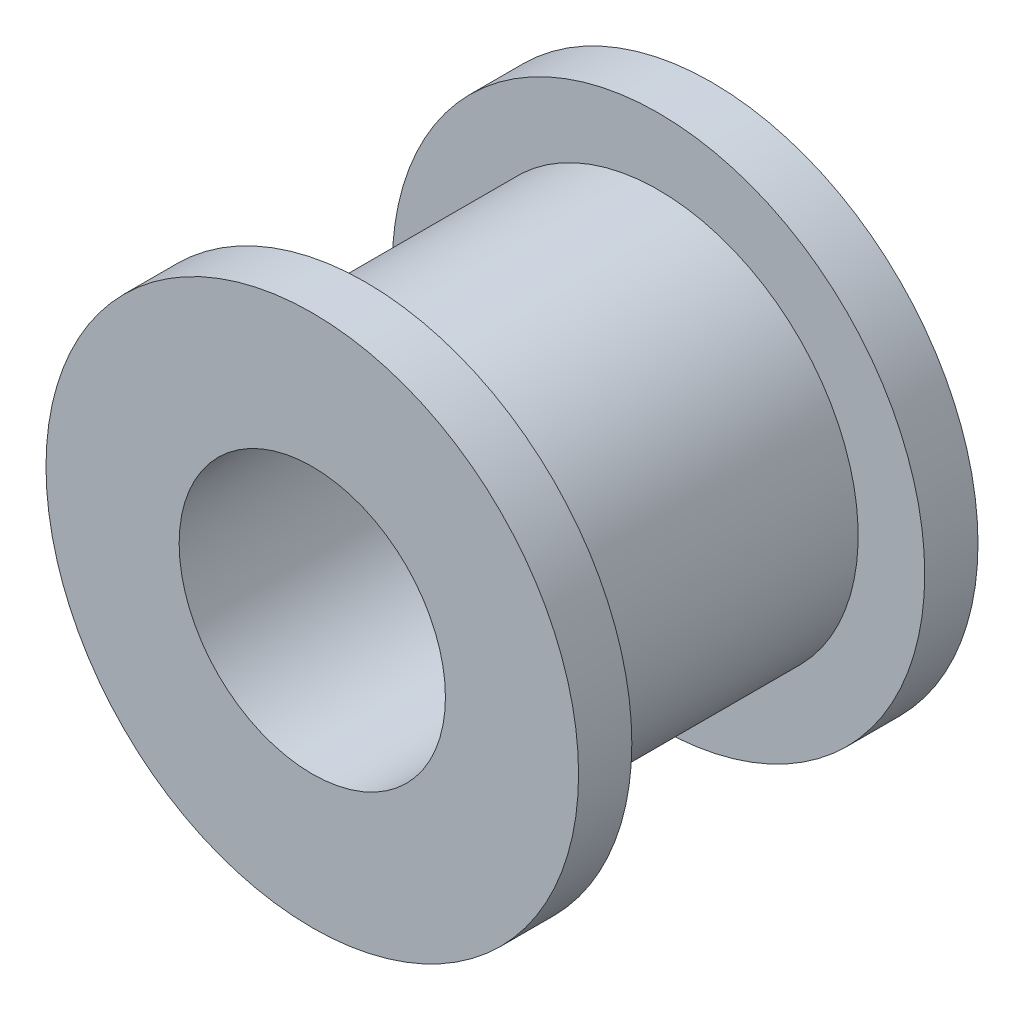
SolidWorks part; units mm, degrees
material "Nylon 6/10"
ref_plane "Front Plane" through (0, 0, 0) normal (0, 0, 1) x (1, 0, 0)
ref_plane "Top Plane" through (0, 0, 0) normal (0, 1, 0) x (1, 0, 0)
ref_plane "Right Plane" through (0, 0, 0) normal (1, 0, 0) x (0, 0, -1)
sketch "Sketch1" plane through (0, 0, 0) normal (0, 0, 1) x (1, 0, 0)
  circle A0 centre (0, 0) radius 5
  circle A1 centre (0, 0) radius 7.5
  dimension "D1" = 10
  dimension "D2" = 15
extrude "Boss-Extrude1" add sketch "Sketch1" along normal blind 11
sketch "Sketch2" plane through (0, 0, 11) normal (0, 0, 1) x (1, 0, 0)
  circle A0 centre (0, 0) radius 10
  circle A1 centre (0, 0) radius 5
  dimension "D1" = 20
extrude "Boss-Extrude2" add sketch "Sketch2" along normal blind 2
sketch "Sketch3" plane through (0, 0, 0) normal (0, 0, -1) x (-1, 0, 0)
  circle A0 centre (0, 0) radius 5
  circle A1 centre (0, 0) radius 10
extrude "Boss-Extrude3" add sketch "Sketch3" along normal blind 2
